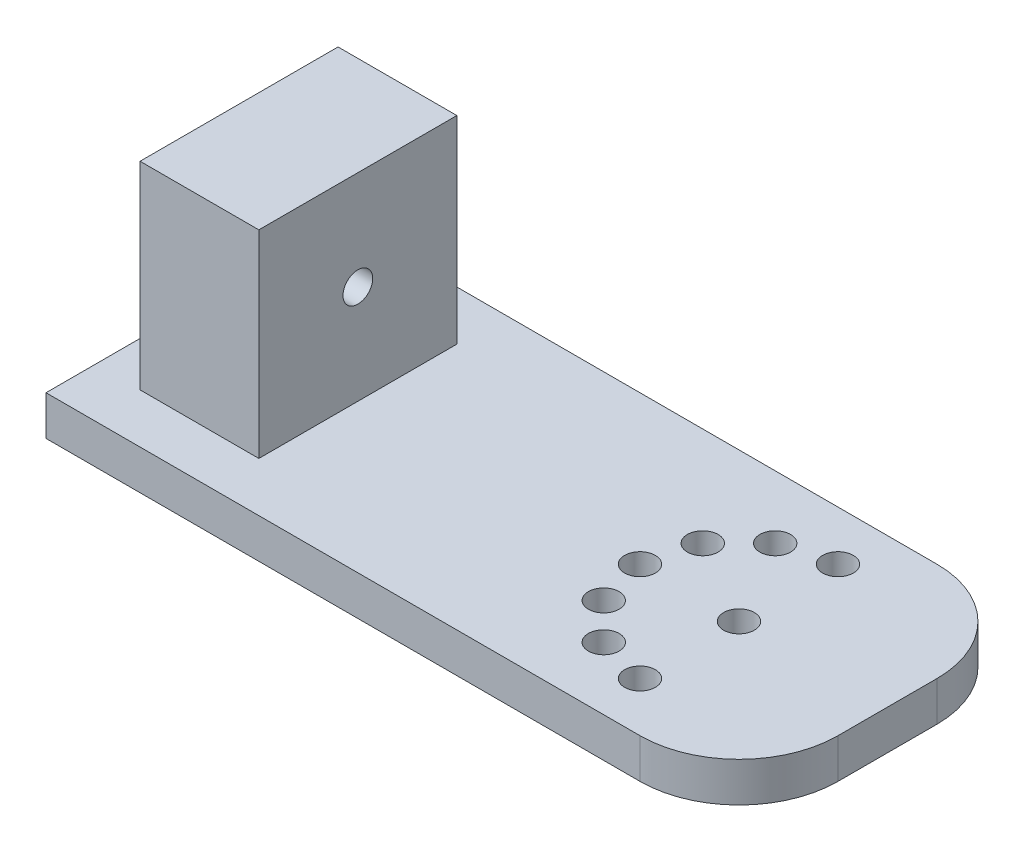
SolidWorks part; units mm, degrees
ref_plane "前视基准面" through (0, 0, 0) normal (0, 0, 1) x (1, 0, 0)
ref_plane "上视基准面" through (0, 0, 0) normal (0, 1, 0) x (1, 0, 0)
ref_plane "右视基准面" through (0, 0, 0) normal (1, 0, 0) x (0, 0, -1)
sketch "草图1" plane through (0, 0, 0) normal (0, 1, 0) x (1, 0, 0)
  line L1 (0, 0) -> (70, 0)
  line L2 (0, 0) -> (0, -30)
  line L3 (0, -30) -> (70, -30)
  line L4 (70, 0) -> (70, -30)
extrude "凸台-拉伸1" add sketch "草图1" along normal blind 4
sketch "草图2" plane through (0, 4, 0) normal (0, 1, 0) x (1, 0, 0)
  line L0 (70, 0) -> (0, 0) construction
  line L1 (4.5, -5) -> (16.5, -5)
  line L2 (4.5, -5) -> (4.5, -25)
  line L3 (4.5, -25) -> (16.5, -25)
  line L4 (16.5, -5) -> (16.5, -25)
  line L5 (0, 0) -> (0, -30) construction
  dimension "D1" = 5
  dimension "D2" = 4.5
extrude "凸台-拉伸2" add sketch "草图2" along normal blind 20
sketch "草图7" plane through (16.5, 0, 0) normal (1, 0, 0) x (0, 0, -1)
  line L0 (-25, 24) -> (-25, 4) construction
  line L1 (-25, 4) -> (-5, 4) construction
  circle A0 centre (-15, 14) radius 1.5
  dimension "D1" = 10
  dimension "D2" = 10
extrude "切除-拉伸2" cut sketch "草图7" against normal blind 12
sketch "草图11" plane through (0, 4, 0) normal (0, 1, 0) x (1, 0, 0)
  line L0 (70, -30) -> (70, 0) construction
  line L1 (0, -30) -> (70, -30) construction
  line L2 (55, -5) -> (55, -15) construction
  line L3 (55, -15) -> (60, -6.3397) construction
  line L4 (55, -15) -> (63.6603, -10) construction
  line L5 (60, -23.6603) -> (55, -15) construction
  line L6 (55, -15) -> (63.6603, -20) construction
  line L7 (65, -15) -> (45, -15) construction
  line L8 (55, -15) -> (55, -25) construction
  line L10 (55, -15) -> (46.3397, -20) construction
  line L11 (50, -23.6603) -> (55, -15) construction
  line L12 (55, -15) -> (46.3397, -10) construction
  line L13 (55, -15) -> (50, -6.3397) construction
  circle A0 centre (55, -15) radius 1.55
  circle A1 centre (55, -15) radius 10 construction
  circle A9 centre (50, -23.6603) radius 1.55
  circle A10 centre (46.3397, -20) radius 1.55
  circle A11 centre (46.3397, -10) radius 1.55
  circle A12 centre (50, -6.3397) radius 1.55
  circle A13 centre (45, -15) radius 1.55
  circle A14 centre (55, -5) radius 1.55
  circle A15 centre (55, -25) radius 1.55
  dimension "D1" = 15
  dimension "D3" = 30
  dimension "D8" = 30
  dimension "D4" = 3.1
  dimension "D5" = 30
  dimension "D6" = 20
  dimension "D2" = 15
  dimension "D7" = 30
  dimension "D9" = 30
extrude "切除-拉伸4" cut sketch "草图11" against normal blind 50
fillet "圆角1" radius 10 1 edges at (70, 2, 30)
fillet "圆角2" radius 10 1 edges at (70, 2, 0)
